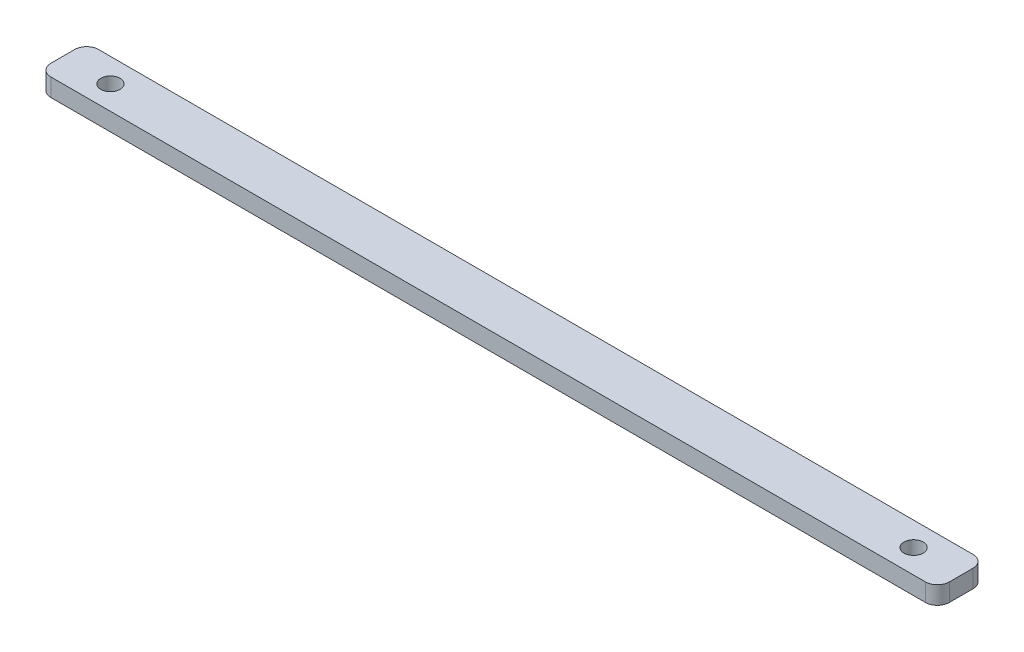
SolidWorks part; units mm, degrees
ref_plane "Front Plane" through (0, 0, 0) normal (0, 0, 1) x (1, 0, 0)
ref_plane "Top Plane" through (0, 0, 0) normal (0, 1, 0) x (1, 0, 0)
ref_plane "Right Plane" through (0, 0, 0) normal (1, 0, 0) x (0, 0, -1)
sketch "Sketch1" plane through (0, 0, 0) normal (0, 1, 0) x (1, 0, 0)
  line L1 (75.5, -4) -> (-75.5, -4)
  line L2 (75.5, -4) -> (75.5, 4)
  line L3 (75.5, 4) -> (-75.5, 4)
  line L4 (-75.5, -4) -> (-75.5, 4)
  line L5 (0, 4) -> (0, -4) construction
  line L6 (75.5, 0) -> (-75.5, 0) construction
  circle A0 centre (-67.5, 0) radius 1.621
  circle A1 centre (67.5, 0) radius 1.621
  point P0 (0, 0)
  dimension "D1" = 3.242
  dimension "D2" = 135
  dimension "D3" = 67.5
  dimension "D4" = 8
  dimension "D5" = 8
extrude "Boss-Extrude1" add sketch "Sketch1" along normal blind 3
fillet "Fillet1" radius 2 4 edges at (-75.5, 1.5, 4) (-75.5, 1.5, -4) (75.5, 1.5, -4) (75.5, 1.5, 4)
